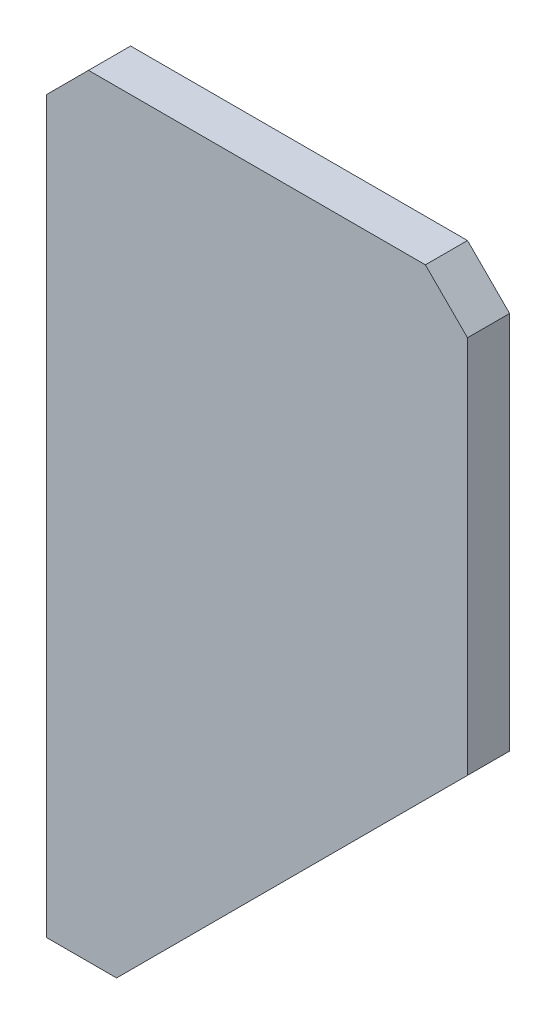
SolidWorks part; units mm, degrees
ref_plane "Front Plane" through (0, 0, 0) normal (0, 0, 1) x (1, 0, 0)
ref_plane "Top Plane" through (0, 0, 0) normal (0, 1, 0) x (1, 0, 0)
ref_plane "Right Plane" through (0, 0, 0) normal (1, 0, 0) x (0, 0, -1)
sketch "Sketch1" plane through (0, 0, 0) normal (0, 0, 1) x (1, 0, 0)
  line L1 (-15, -27.5) -> (15, -27.5)
  line L2 (-15, -27.5) -> (-15, 27.5)
  line L3 (-15, 27.5) -> (15, 27.5)
  line L4 (15, -27.5) -> (15, 27.5)
  line L5 (-15, -27.5) -> (15, 27.5) construction
  line L6 (-15, 27.5) -> (15, -27.5) construction
  point P0 (0, 0)
  dimension "D1" = 55
  dimension "D2" = 30
extrude "Boss-Extrude1" add sketch "Sketch1" along normal mid plane 3
chamfer "Chamfer1" distance 3 angle 45 2 edges at (-15, 27.5, 0) (15, 27.5, 0)
chamfer "Chamfer2" distance 25 distance2 25 1 edges at (15, -27.5, 0)
